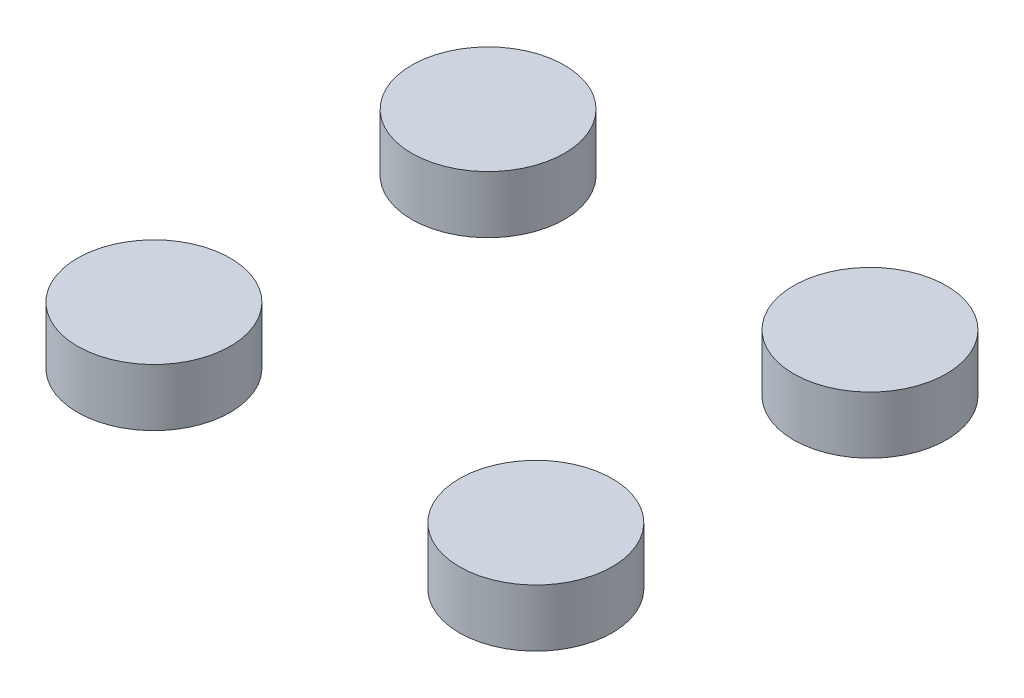
SolidWorks part; units mm, degrees
ref_plane "Front Plane" through (0, 0, 0) normal (0, 0, 1) x (1, 0, 0)
ref_plane "Top Plane" through (0, 0, 0) normal (0, 1, 0) x (1, 0, 0)
ref_plane "Right Plane" through (0, 0, 0) normal (1, 0, 0) x (0, 0, -1)
sketch "Sketch1" plane through (0, 0, 0) normal (0, 1, 0) x (1, 0, 0)
  circle A0 centre (-400, 350) radius 160
extrude "Boss-Extrude1" add sketch "Sketch1" along normal blind 120 from offset 1440
sketch "Sketch2" plane through (0, 0, 0) normal (0, 1, 0) x (1, 0, 0)
  circle A0 centre (-400, -350) radius 160
extrude "Boss-Extrude2" add sketch "Sketch2" along normal blind 120 from offset 1440
sketch "Sketch3" plane through (0, 0, 0) normal (0, 1, 0) x (1, 0, 0)
  circle A0 centre (400, 350) radius 160
extrude "Boss-Extrude3" add sketch "Sketch3" along normal blind 120 from offset 1440
sketch "Sketch4" plane through (0, 0, 0) normal (0, 1, 0) x (1, 0, 0)
  circle A0 centre (400, -350) radius 160
extrude "Boss-Extrude4" add sketch "Sketch4" along normal blind 120 from offset 1440
